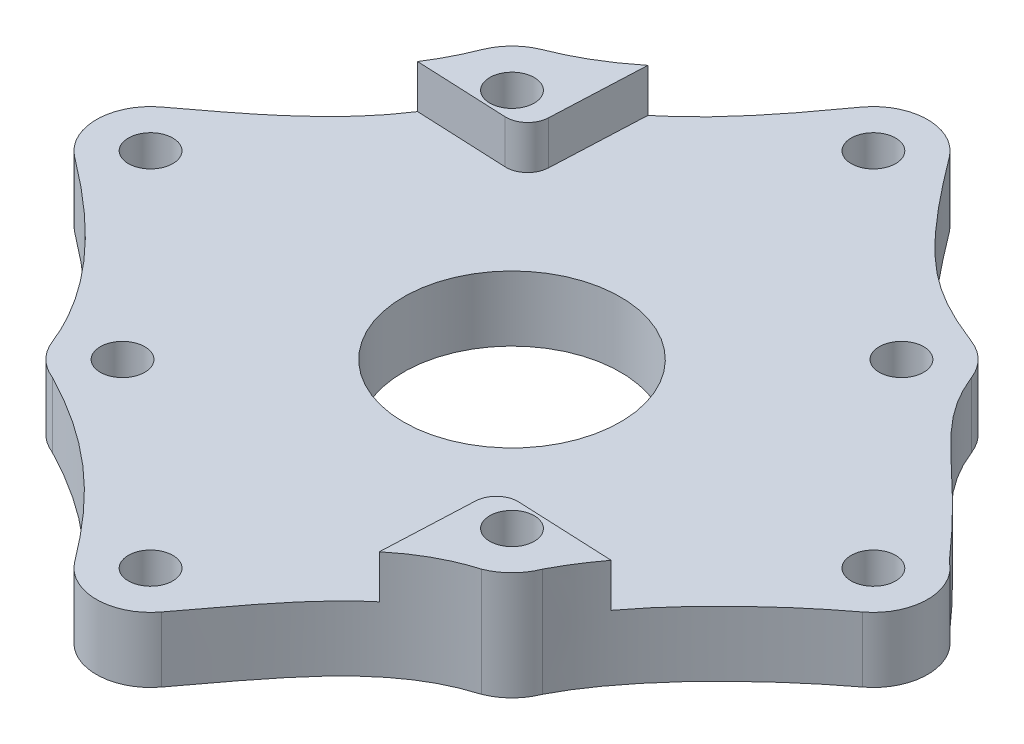
SolidWorks part; units mm, degrees
ref_plane "Alzado" through (0, 0, 0) normal (0, 0, 1) x (1, 0, 0)
ref_plane "Planta" through (0, 0, 0) normal (0, 1, 0) x (1, 0, 0)
ref_plane "Vista lateral" through (0, 0, 0) normal (1, 0, 0) x (0, 0, -1)
sketch "Sketch1" plane through (0, 0, 0) normal (0, 1, 0) x (1, 0, 0)
  line L0 (17.5009, -17.5009) -> (-17.5009, 17.5009) construction
  line L1 (0, 0) -> (0, 33.333) construction
  line L2 (-17.9605, -17.9605) -> (17.9605, 17.9605) construction
  circle A0 centre (0, 0) radius 10
  circle A1 centre (0, 33.333) radius 2.05
  circle A2 centre (33.333, 0) radius 2.05
  circle A3 centre (0, -33.333) radius 2.05
  circle A4 centre (-33.333, 0) radius 2.05
  circle A5 centre (-17.5009, 17.5009) radius 2.1
  circle A6 centre (17.9605, 17.9605) radius 2.1
  circle A7 centre (17.5009, -17.5009) radius 2.1
  circle A8 centre (-17.9605, -17.9605) radius 2.1
  point P14 (0, 0)
  point P17 (0, 0)
  point P19 (0, 0)
  point P27 (0, 0)
  dimension "D1" = 4
  dimension "D3" = 45
  dimension "D7" = 4.1
  dimension "D8" = 4.2
  dimension "D9" = 20
  dimension "D10" = 2
  dimension "D2" = 45
  dimension "D4" = 49.5
  dimension "D5" = 50.8
  dimension "D6" = 47.14
sketch "Sketch2" plane through (0, 0, 0) normal (0, 1, 0) x (1, 0, 0)
  line L1 (-17.9605, -17.9605) -> (17.9605, 17.9605) construction
  line L2 (17.5009, -17.5009) -> (-17.5009, 17.5009) construction
  line L3 (0, 0) -> (0, 33.333) construction
  circle A0 centre (0, 33.333) radius 2.05
  arc A1 (4, 36.333) -> (-4, 36.333) centre (0, 33.333) ccw
  circle A2 centre (0, 33.333) radius 2.05 construction
  circle A4 centre (33.333, 0) radius 2.05
  arc A5 (-4, -36.333) -> (4, -36.333) centre (0, -33.333) ccw
  circle A6 centre (0, -33.333) radius 2.05
  arc A7 (-36.333, 4) -> (-36.333, -4) centre (-33.333, 0) ccw
  circle A8 centre (-33.333, 0) radius 2.05
  arc A9 (36.333, -4) -> (36.333, 4) centre (33.333, 0) ccw
  circle A11 centre (0, 0) radius 10
  circle A12 centre (0, 0) radius 10 construction
  arc A13 (-19.327, 22.1555) -> (-22.1555, 19.327) centre (-17.5009, 17.5009) ccw
  arc A14 (22.6151, 19.7867) -> (19.7867, 22.6151) centre (17.9605, 17.9605) ccw
  arc A15 (19.327, -22.1555) -> (22.1555, -19.327) centre (17.5009, -17.5009) ccw
  arc A16 (-22.6151, -19.7867) -> (-19.7867, -22.6151) centre (-17.9605, -17.9605) ccw
  arc A17 (36.2461, -4.0638) -> (36.3257, 4.0055) centre (33.333, 0) ccw [skipped]
  circle A18 centre (-17.5009, 17.5009) radius 2.05
  circle A19 centre (-17.9605, -17.9605) radius 2.05
  circle A20 centre (17.9605, 17.9605) radius 2.05
  circle A21 centre (17.5009, -17.5009) radius 2.05
  spline S0 degree 3 poles (-36.333, 4) (-30.5051, 8.371) (-24.8398, 12.485) (-22.1555, 19.327) knots 0 0 0 0 1 1 1 1
  spline S1 degree 3 poles (-19.327, 22.1555) (-12.7636, 24.7306) (-8.4275, 30.1565) (-4, 36.333) knots 0 0 0 0 1 1 1 1
  spline S2 degree 3 poles (-36.333, -4) (-30.1142, -8.6641) (-24.9429, -13.8534) (-22.6151, -19.7867) knots 0 0 0 0 1 1 1 1
  spline S3 degree 3 poles (-19.7867, -22.6151) (-12.8291, -26.2052) (-8.518, -30.3091) (-4, -36.333) knots 0 0 0 0 1 1 1 1
  spline S4 degree 3 poles (4, -36.333) (8.9867, -29.6841) (12.8296, -24.0738) (19.327, -22.1555) knots 0 0 0 0 1 1 1 1
  spline S5 degree 3 poles (22.1555, -19.327) (25.0184, -13.753) (31.3543, -7.734) (36.333, -4) knots 0 0 0 0 1 1 1 1
  spline S6 degree 3 poles (36.333, 4) (28.975, 12.4348) (24.8494, 14.0919) (22.6151, 19.7867) knots 0 0 0 0 1 1 1 1
  spline S7 degree 3 poles (4, 36.333) (10.9028, 27.1293) (13.6732, 25.0136) (19.7867, 22.6151) knots 0 0 0 0 1 1 1 1
  point P18 (0, 0)
  point P26 (-38.333, 0)
  point P28 (-21.496, -21.496)
  point P35 (0, -38.333)
  point P39 (21.0364, -21.0364)
  point P43 (-21.0364, 21.0364)
  point P47 (0, 38.333)
  point P53 (38.333, 0)
  point P62 (21.496, 21.496)
  point P67 (0, 0)
  dimension "D1" = 10
  dimension "D3" = 10
  dimension "D5" = 4
  dimension "D10" = 4
  dimension "D12" = 2
  dimension "D4" = 4
  dimension "D6" = 8
  dimension "D7" = 8
  dimension "D8" = 8
  dimension "D9" = 8
  dimension "D11" = 4
  dimension "D2" = 4
extrude "Boss-Extrude1" add sketch "Sketch2" along normal blind 6
sketch "Sketch4" plane through (0, 6, 0) normal (0, 1, 0) x (1, 0, 0)
  line L1 (15.7078, -15.0684) -> (24.6064, -15.4662)
  line L2 (17.5009, -17.5009) -> (-17.5009, 17.5009) construction
  line L4 (13.6204, -16.977) -> (13.2404, -25.4761)
  line L7 (-13.6086, 17.0734) -> (-13.4394, 25.5792) [skipped]
  line L8 (-15.648, 15.1136) -> (-24.5538, 15.2907) [skipped]
  line L9 (-13.2284, 25.7569) -> (-13.6204, 16.9773)
  line L10 (-15.7076, 15.0685) -> (-24.1527, 15.4455)
  arc A0 (13.6204, -16.977) -> (15.7078, -15.0684) centre (15.6184, -17.0664) cw
  arc A1 (19.327, -22.1555) -> (22.1555, -19.327) centre (17.5009, -17.5009) ccw construction
  arc A2 (19.327, -22.1555) -> (22.1555, -19.327) centre (17.5009, -17.5009) ccw
  circle A3 centre (17.5009, -17.5009) radius 2.05 construction
  circle A4 centre (17.5009, -17.5009) radius 2.05
  circle A6 centre (-17.5009, 17.5009) radius 2.05 construction
  circle A7 centre (-17.5009, 17.5009) radius 2.05 construction
  circle A10 centre (-17.5009, 17.5009) radius 2.05
  arc A12 (-19.4419, 22.1088) -> (-22.1993, 19.2111) centre (-17.5009, 17.5009) ccw [skipped]
  arc A13 (-13.6086, 17.0734) -> (-15.648, 15.1136) centre (-15.6082, 17.1132) cw [skipped]
  arc A14 (-13.6204, 16.9773) -> (-15.7076, 15.0685) centre (-15.6184, 17.0665) cw
  arc A15 (-19.327, 22.1555) -> (-22.1555, 19.327) centre (-17.5009, 17.5009) ccw construction
  arc A16 (-19.327, 22.1555) -> (-22.1555, 19.327) centre (-17.5009, 17.5009) ccw
  spline S0 degree 3 poles (-1838.5231, 723.1196) (1623.9389, -1133.9193) (-1530.6734, 1215.9153) (1603.598, -1242.5506) knots -7.406882 -7.406882 -7.406882 -7.406882 7.626851 7.626851 7.626851 7.626851 only from (4, -36.333) to (19.327, -22.1555) construction
  spline S1 degree 3 poles (1869.6336, 742.3025) (-1898.3331, -1034.7299) (1892.936, 1139.358) (-1614.396, -1132.4627) knots -6.680174 -6.680174 -6.680174 -6.680174 7.863092 7.863092 7.863092 7.863092 only from (22.1555, -19.327) to (36.333, -4) construction
  spline S2 degree 3 poles (13.2404, -25.4761) (15.048, -23.983) (17.0202, -22.8366) (19.327, -22.1555) knots 0.644965 0.644965 0.644965 0.644965 1 1 1 1
  spline S3 degree 3 poles (22.1555, -19.327) (22.8101, -18.0525) (23.6463, -16.7547) (24.6064, -15.4662) knots 0 0 0 0 0.228659 0.228659 0.228659 0.228659
  spline S4 degree 3 poles (1680.05, -1031.062) (-1477.5505, 1402.0264) (1419.6327, -1401.0692) (-1526.1142, 1335.9804) knots -8.737944 -8.737944 -8.737944 -8.737944 8.50971 8.50971 8.50971 8.50971 only from (-4, 36.333) to (-19.327, 22.1555) construction
  spline S5 degree 3 poles (-1323.254, 1536.7193) (1405.0875, -1412.2702) (-1446.9266, 1442.7028) (1161.9555, -1593.1327) knots -6.909908 -6.909908 -6.909908 -6.909908 8.854836 8.854836 8.854836 8.854836 only from (-22.1555, 19.327) to (-36.333, 4) construction
  spline S6 degree 3 poles (-13.2284, 25.7569) (-15.0593, 24.2741) (-17.0604, 23.0448) (-19.327, 22.1555) knots 0.654651 0.654651 0.654651 0.654651 1 1 1 1
  spline S7 degree 3 poles (-22.1555, 19.327) (-22.7045, 17.9276) (-23.3783, 16.6423) (-24.1527, 15.4455) knots 0 0 0 0 0.204539 0.204539 0.204539 0.204539
  point P28 (0.2169, 0.2169)
  dimension "D1" = 42.44
  dimension "D2" = 2.35
  dimension "D5" = 2
  dimension "D6" = 2
  dimension "D7" = 2
  dimension "D3" = 90
  dimension "D4" = 3.9
  dimension "D8" = 42.444
  dimension "D9" = 90
  dimension "D10" = 2.35
  dimension "D11" = 3.9
extrude "Boss-Extrude2" add sketch "Sketch4" along normal blind 4
